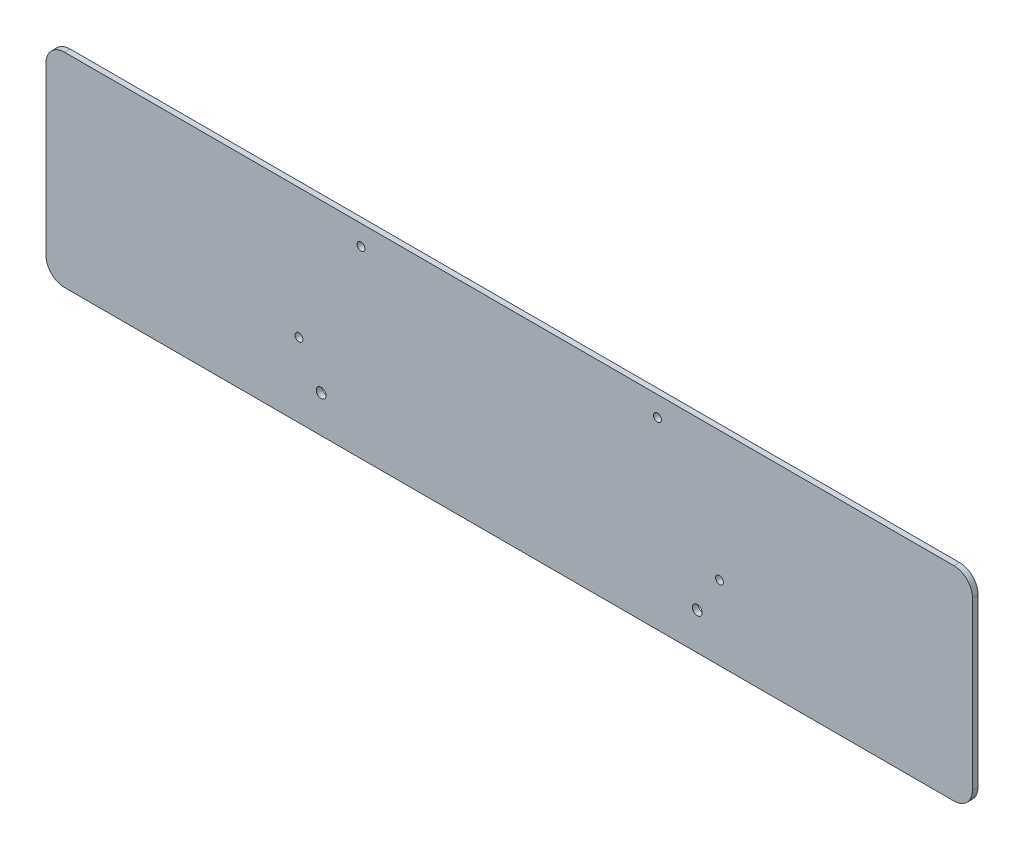
SolidWorks part; units mm, degrees
ref_plane "Front Plane" through (0, 0, 0) normal (0, 0, 1) x (1, 0, 0)
ref_plane "Top Plane" through (0, 0, 0) normal (0, 1, 0) x (1, 0, 0)
ref_plane "Right Plane" through (0, 0, 0) normal (1, 0, 0) x (0, 0, -1)
sketch "Sketch1" plane through (0, 0, 0) normal (0, 0, 1) x (1, 0, 0)
  line L1 (0, 0) -> (500, 0)
  line L2 (0, 0) -> (0, 110)
  line L3 (0, 110) -> (500, 110)
  line L4 (500, 0) -> (500, 110)
  dimension "D1" = 110
  dimension "D2" = 500
extrude "Boss-Extrude1" add sketch "Sketch1" along normal blind 3
sketch "Sketch2" plane through (0, 0, 3) normal (0, 0, 1) x (1, 0, 0)
  line L0 (0, 0) -> (500, 0) construction
  line L1 (0, 110) -> (0, 0) construction
  line L2 (250, 110) -> (250, 0) construction
  line L3 (500, 110) -> (0, 110) construction
  circle A0 centre (148.5, 20) radius 2.65
  circle A1 centre (136.5, 40) radius 2.125
  circle A3 centre (363.5, 40) radius 2.125
  circle A4 centre (351.5, 20) radius 2.65
  dimension "D3" = 5.3
  dimension "D6" = 4.25
  dimension "D1" = 20
  dimension "D2" = 148.5
  dimension "D4" = 136.5
  dimension "D5" = 40
extrude "Cut-Extrude1" cut sketch "Sketch2" against normal blind 10
sketch "Sketch3" plane through (0, 0, 3) normal (0, 0, 1) x (1, 0, 0)
  line L0 (250, 110) -> (250, 0) construction
  line L1 (500, 110) -> (0, 110) construction
  line L2 (0, 0) -> (500, 0) construction
  circle A0 centre (170, 99.2) radius 2.125
  circle A1 centre (330, 99.2) radius 2.125
  dimension "D1" = 4.25
  dimension "D2" = 80
  dimension "D3" = 10.8
extrude "Cut-Extrude2" cut sketch "Sketch3" against normal blind 10
fillet "Fillet1" radius 10 4 edges at (0, 0, 1.5) (0, 110, 1.5) (500, 0, 1.5) (500, 110, 1.5)
